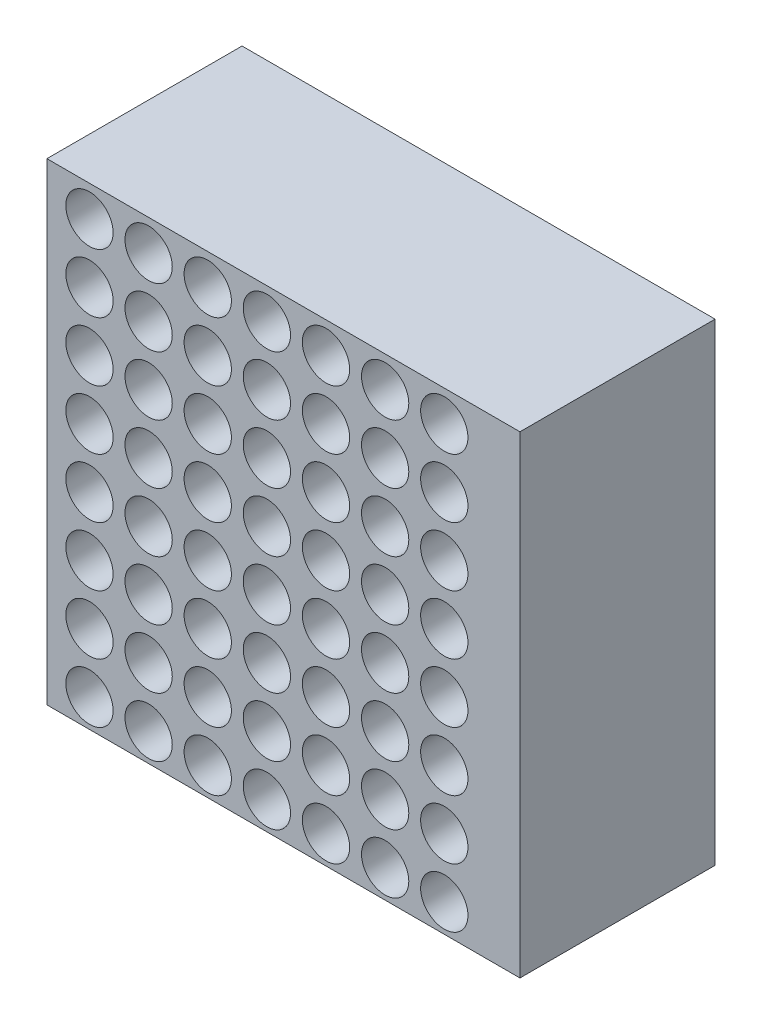
SolidWorks part; units mm, degrees
ref_plane "Front Plane" through (0, 0, 0) normal (0, 0, 1) x (1, 0, 0)
ref_plane "Top Plane" through (0, 0, 0) normal (0, 1, 0) x (1, 0, 0)
ref_plane "Right Plane" through (0, 0, 0) normal (1, 0, 0) x (0, 0, -1)
sketch "Sketch1" plane through (0, 0, 0) normal (0, 0, 1) x (1, 0, 0)
  line L1 (-68.2092, 36.9128) -> (11.7908, 36.9128)
  line L2 (-68.2092, 36.9128) -> (-68.2092, -43.0872)
  line L3 (-68.2092, -43.0872) -> (11.7908, -43.0872)
  line L4 (11.7908, 36.9128) -> (11.7908, -43.0872)
  dimension "D1" = 80
  dimension "D2" = 80
extrude "Boss-Extrude1" add sketch "Sketch1" along normal blind 33 contours L2 L1 L4 L3
sketch "Sketch2" plane through (0, 0, 33) normal (0, 0, 1) x (1, 0, 0)
  circle A0 centre (-61.0094, 31.6654) radius 4
  dimension "D1" = 8
extrude "Cut-Extrude1" cut sketch "Sketch2" against normal blind 33
pattern_linear "LPattern1" count 8 spacing 10 along (0, -1, 0) count 7 spacing 10 along (1, 0, 0) of "Cut-Extrude1"
